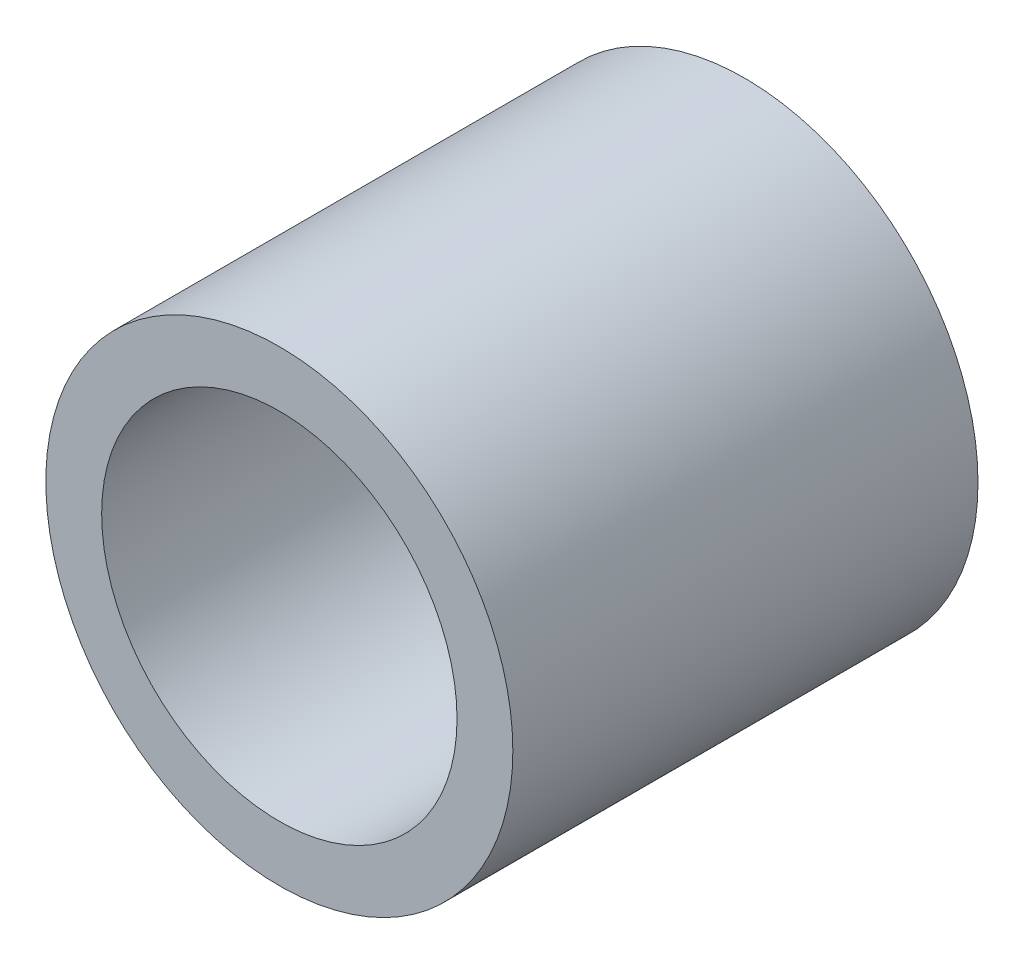
SolidWorks part; units mm, degrees
ref_plane "Front Plane" through (0, 0, 0) normal (0, 0, 1) x (1, 0, 0)
ref_plane "Top Plane" through (0, 0, 0) normal (0, 1, 0) x (1, 0, 0)
ref_plane "Right Plane" through (0, 0, 0) normal (1, 0, 0) x (0, 0, -1)
sketch "Sketch1" plane through (0, 0, 0) normal (0, 0, 1) x (1, 0, 0)
  circle A0 centre (0, 0) radius 3.1877
  circle A1 centre (0, 0) radius 2.4257
  dimension "D1" = 6.3754
  dimension "ID" = 4.8514
extrude "Extrude1" add sketch "Sketch1" along normal mid plane 6.35
sketch "Sketch2" plane through (0, 0, 0) normal (1, 0, 0) x (0, 0, -1)
  line L0 (-3.175, -2.4257) -> (3.175, -2.4257) construction
  line L3 (3.175, 2.4257) -> (-3.175, 2.4257) construction
  line L5 (-3.175, -2.4257) -> (3.175, -2.4257)
  line L6 (3.175, 2.4257) -> (-3.175, 2.4257)
sketch "Sketch4" plane through (0, 0, 3.175) normal (0, 0, 1) x (1, 0, 0)
  line L0 (0, 0) -> (-1.7152, 1.7152)
  line L1 (0, -3.5065) -> (0, 3.5065) construction
  circle A0 centre (0, 0) radius 2.4257 construction
  dimension "D1" = 45
